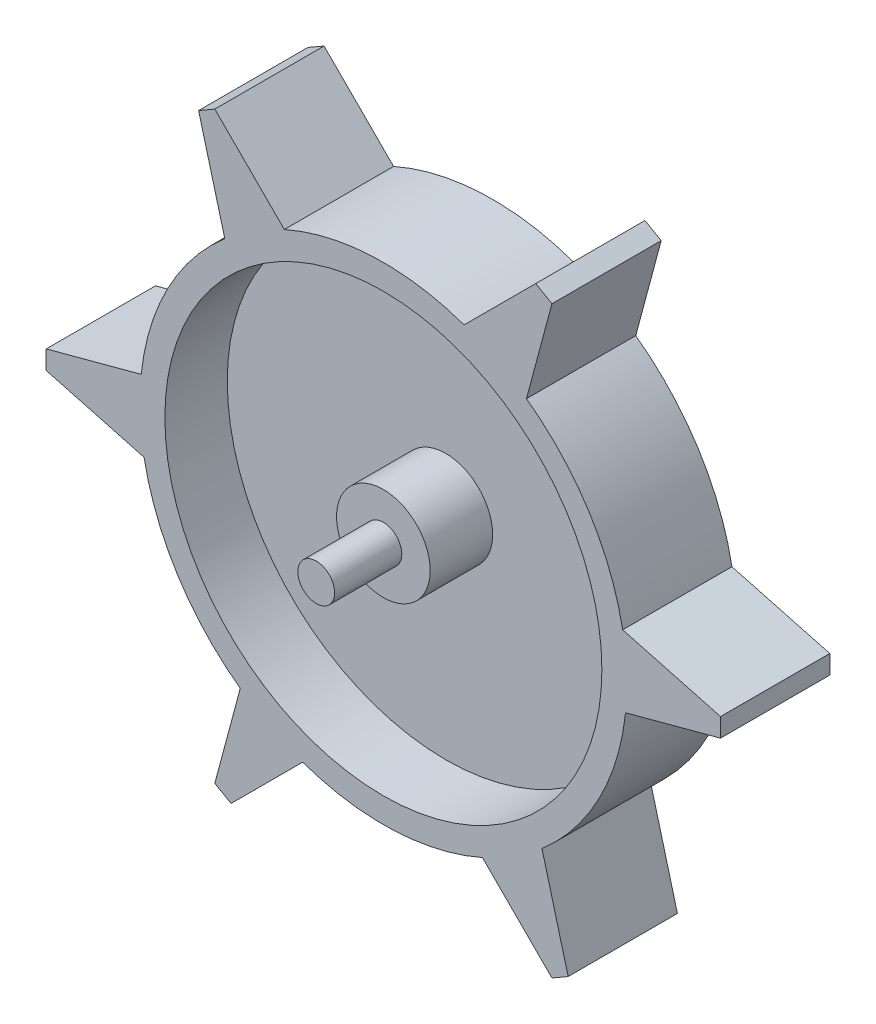
SolidWorks part; units mm, degrees
ref_plane "Front Plane" through (0, 0, 0) normal (0, 0, 1) x (1, 0, 0)
ref_plane "Top Plane" through (0, 0, 0) normal (0, 1, 0) x (1, 0, 0)
ref_plane "Right Plane" through (0, 0, 0) normal (1, 0, 0) x (0, 0, -1)
sketch "Sketch1" plane through (0, 0, 0) normal (0, 0, 1) x (1, 0, 0)
  line L0 (-54, -3) -> (-38.3298, -7.1988)
  line L1 (-54, 0) -> (-54, -3)
  line L21 (-54, 0) -> (-38.7864, 4.0765)
  circle A0 centre (0, 0) radius 39
  point P34 (0, 0)
  dimension "D1" = 78
  dimension "D2" = 15
  dimension "D3" = 3
  dimension "D5" = 15
extrude "Boss-Extrude1" add sketch "Sketch1" along normal blind 17.5
sketch "Sketch3" plane through (0, 0, 17.5) normal (0, 0, 1) x (1, 0, 0)
  circle A0 centre (0, 0) radius 2.95
  dimension "D1" = 5.9
extrude "Boss-Extrude5" add sketch "Sketch3" along direction (0, 0, 1) on the side against the normal blind 28.25 and the other way blind 10.75
sketch "Sketch2" plane through (0, 0, 0) normal (0, 0, -1) x (-1, 0, 0)
  line L1 (-1.2238, -1.18) -> (1.2238, -1.18)
  arc A0 (1.2238, -1.18) -> (-1.2238, -1.18) centre (0, 0) ccw
  dimension "D1" = 3.4
  dimension "D2" = 1.18
extrude "Cut-Extrude1" cut sketch "Sketch2" against normal blind 7.5 from surface at 10.75 starting at face at (2.95, 0, -10.75)
pattern_circular "CirPattern1" count 6 over 360 about axis through (0, 0, 0) along (0, 0, 1) of "Boss-Extrude1"
sketch "Sketch4" plane through (0, 0, 17.5) normal (0, 0, 1) x (1, 0, 0)
  circle A0 centre (0, 0) radius 35
  circle A1 centre (0, 0) radius 7.5
  dimension "D1" = 70
  dimension "D2" = 15
extrude "Cut-Extrude2" cut sketch "Sketch4" against normal blind 10
